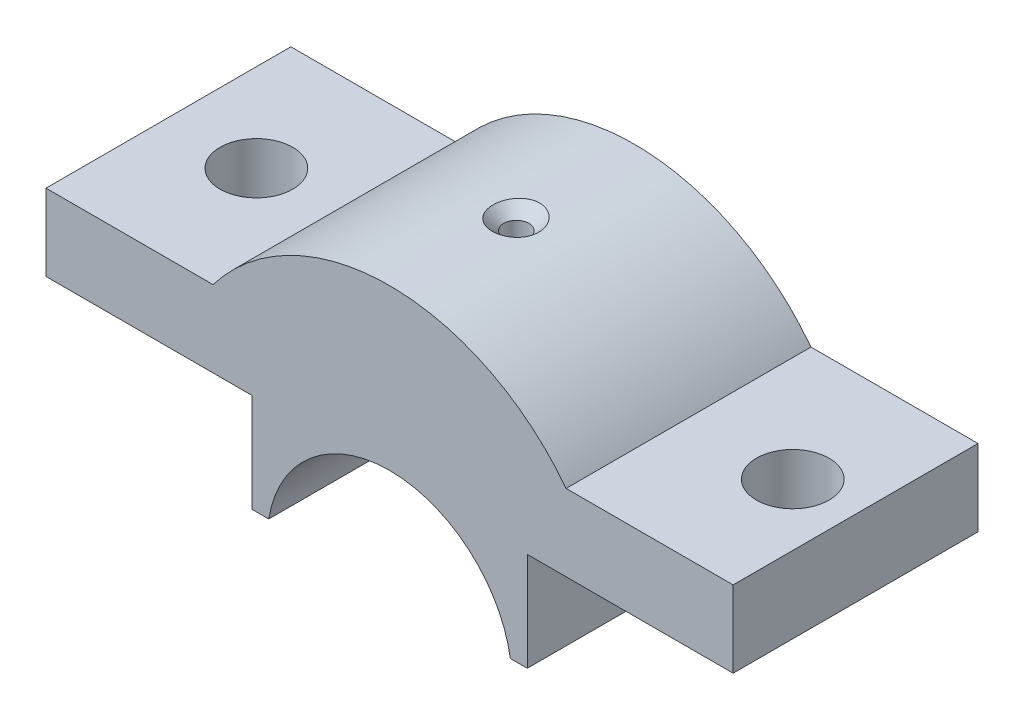
SolidWorks part; units mm, degrees
ref_plane "Front Plane" through (0, 0, 0) normal (0, 0, 1) x (1, 0, 0)
ref_plane "Top Plane" through (0, 0, 0) normal (0, 1, 0) x (1, 0, 0)
ref_plane "Right Plane" through (0, 0, 0) normal (1, 0, 0) x (0, 0, -1)
sketch "Sketch1" plane through (0, 0, 0) normal (0, 0, 1) x (1, 0, 0)
  line L0 (0, 0) -> (0, 20)
  line L1 (0, 20) -> (43.6607, 20)
  line L5 (53.7976, 0) -> (0, 0)
  line L6 (53.7976, 0) -> (53.7976, -25.7784)
  line L7 (53.7976, -25.7784) -> (58.2242, -25.7784)
  line L8 (125.7976, -25.7784) -> (121.371, -25.7784)
  line L9 (125.7976, 0) -> (125.7976, -25.7784)
  line L10 (179.5952, 0) -> (179.5952, 20)
  line L11 (125.7976, 0) -> (179.5952, 0)
  line L12 (179.5952, 20) -> (135.9345, 20)
  arc A0 (43.6607, 20) -> (135.9345, 20) centre (89.7976, -15.148) cw
  arc A1 (121.371, -25.7784) -> (58.2242, -25.7784) centre (89.7976, -30.9859) ccw
  point P9 (63.4208, -25.7784)
  point P11 (0, 0)
  point P12 (43.6607, 20)
  point P14 (0, 0)
  dimension "D2" = 32
  dimension "D3" = 58
  dimension "D1" = 20
extrude "Boss-Extrude1" add sketch "Sketch1" along normal blind 64
hole_wizard "Ø1.0mm Dowel Hole1" positions "Sketch2" profile "Sketch3" hole size "Ø1.0" standard "ISO"
sketch "Sketch2" plane through (0, 20, 0) normal (0, 1, 0) x (1, 0, 0)
  line L0 (43.6607, 0) -> (0, 0) construction
  point P0 (22.988, -32)
  point P3 (163.4547, -32.2776)
  point P12 (0, -32.0925)
  point P17 (0, 0)
  point P18 (0, 0)
  dimension "D1" = 32
sketch "Sketch3" plane through (22.988, 20, 32) normal (1, 0, 0) x (0, 0, 1)
  line L0 (0, 0) -> (0, 135.7082)
  line L1 (0, 135.7082) -> (9.5, 130)
  line L2 (9.5, 130) -> (9.5, 0)
  line L5 (9.5, 0) -> (0, 0)
  line L10 (0, 135.7082) -> (-9.5, 130) construction
  line L11 (0, -6.35) -> (0, 107.95) construction
  dimension "Hole Dia." = 19
  dimension "Hole Depth" = 130
  dimension "Drill Angle" = 118
ref_plane "Plane1" through (0, 42.852, 0) normal (0, 1, 0) x (1, 0, 0)
hole_wizard "CSK for M6 Countersunk Flat Head Screw1" positions "Sketch6" profile "Sketch7" countersink size "M6" standard "ISO"
sketch "Sketch6" plane through (0, 42.852, 0) normal (0, 1, 0) x (1, 0, 0)
  line L0 (135.9345, 0) -> (43.6607, 0) construction
  line L1 (135.9345, -64) -> (135.9345, 0) construction
  point P0 (90.9345, -32)
  dimension "D1" = 32
  dimension "D2" = 45
sketch "Sketch7" plane through (90.9345, 42.852, 32) normal (1, 0, 0) x (0, 0, 1)
  line L0 (0, 0) -> (0, 131.9828)
  line L1 (0, 131.9828) -> (3.3, 130)
  line L2 (3.3, 130) -> (3.3, 3)
  line L3 (3.3, 3) -> (6.3, 0)
  line L5 (6.3, 0) -> (0, 0)
  line L6 (-3.3, 3) -> (-6.3, 0) construction
  line L10 (0, 131.9828) -> (-3.3, 130) construction
  line L11 (0, -6.35) -> (0, 107.95) construction
  dimension "Hole Dia." = 6.6
  dimension "Hole Depth" = 130
  dimension "Near C'Sink Dia." = 12.6
  dimension "Near C'Sink Angle" = 90
  dimension "Drill Angle" = 118
